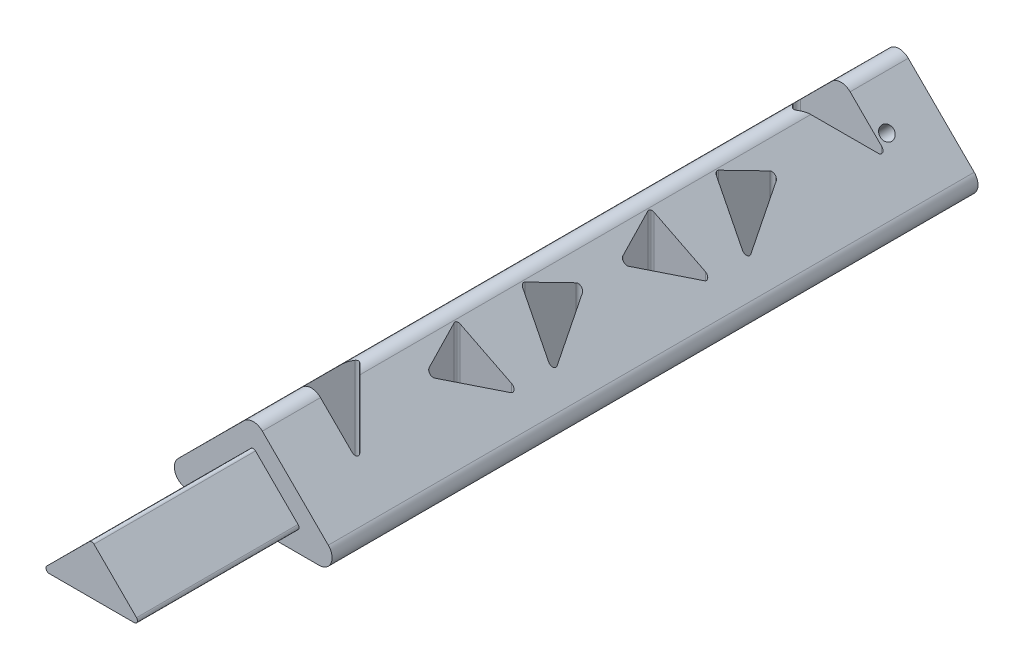
SolidWorks part; units mm, degrees
ref_plane "前视基准面" through (0, 0, 0) normal (0, 0, 1) x (1, 0, 0)
ref_plane "上视基准面" through (0, 0, 0) normal (0, 1, 0) x (1, 0, 0)
ref_plane "右视基准面" through (0, 0, 0) normal (1, 0, 0) x (0, 0, -1)
other "Configuration Table"
sketch "草图1" plane through (0, 0, 0) normal (0, 0, 1) x (1, 0, 0)
  line L0 (-30.1, 0) -> (30.1, 0)
  line L1 (30.1, 0) -> (0, 30.004)
  line L2 (0, 30.004) -> (-30.1, 0)
  dimension "D1" = 42.5
  dimension "D2" = 60.2
extrude "凸台-拉伸1" add sketch "草图1" along normal mid plane 200
fillet "圆角1" radius 4 3 edges at (0, 30.004, 0) (30.1, 0, 0) (-30.1, 0, 0)
sketch "草图2" plane through (0, 0, 100) normal (0, 0, 1) x (1, 0, 0)
  line L0 (15.5819, 6) -> (0, 21.5322)
  line L1 (0, 21.5322) -> (-15.5819, 6)
  line L2 (-15.5819, 6) -> (15.5819, 6)
  line L3 (23.2452, 6.8329) -> (2.8239, 27.1891)
  line L4 (-2.8239, 27.1891) -> (-23.2452, 6.8329)
  line L5 (-20.4213, 0) -> (20.4213, 0)
  line L6 (23.2452, 6.8329) -> (2.8239, 27.1891) construction
  line L7 (-2.8239, 27.1891) -> (-23.2452, 6.8329) construction
  line L8 (-20.4213, 0) -> (20.4213, 0) construction
  arc A0 (0, 21.5322) -> (0, 21.5322) centre (0, 21.5322) ccw
  arc A1 (-15.5819, 6) -> (-15.5819, 6) centre (-15.5819, 6) ccw
  arc A2 (15.5819, 6) -> (15.5819, 6) centre (15.5819, 6) ccw
  arc A3 (2.8239, 27.1891) -> (-2.8239, 27.1891) centre (0, 24.3562) ccw
  arc A4 (-23.2452, 6.8329) -> (-20.4213, 0) centre (-20.4213, 4) ccw
  arc A5 (20.4213, 0) -> (23.2452, 6.8329) centre (20.4213, 4) ccw
  arc A6 (2.8239, 27.1891) -> (-2.8239, 27.1891) centre (0, 24.3562) ccw construction
  arc A7 (-23.2452, 6.8329) -> (-20.4213, 0) centre (-20.4213, 4) ccw construction
  arc A8 (20.4213, 0) -> (23.2452, 6.8329) centre (20.4213, 4) ccw construction
  dimension "D1" = 0
  dimension "D2" = 6
extrude "凸台-拉伸2" add sketch "草图2" along normal blind 50
fillet "圆角2" radius 1 3 edges at (15.5819, 6, 125) (-15.5819, 6, 125) (0, 21.5322, 125)
sketch "草图3" plane through (0, 0, 0) normal (0, 1, 0) x (1, 0, 0)
  line L0 (-15, 82) -> (0, 67)
  line L1 (-2.8239, -100) -> (-2.8239, 100) construction
  line L2 (-15, 82) -> (15, 82)
  line L3 (15, 82) -> (0, 67)
  line L4 (-8, 55) -> (-18, 35)
  line L5 (-18, 35) -> (-2.8239, 40)
  line L6 (-2.8239, 40) -> (-8, 55)
  line L7 (0, -59.243) -> (0, 59.243) construction
  line L8 (2.8239, 40) -> (8, 55)
  line L9 (18, 35) -> (2.8239, 40)
  line L10 (8, 55) -> (18, 35)
  line L14 (-17.9681, 30) -> (0, 30) construction
  line L15 (2.8239, 100) -> (2.8239, -100) construction
  line L16 (8, 5) -> (18, 25)
  line L17 (18, 25) -> (2.8239, 20)
  line L18 (2.8239, 20) -> (8, 5)
  line L19 (-2.8239, 20) -> (-8, 5)
  line L20 (-18, 25) -> (-2.8239, 20)
  line L21 (-8, 5) -> (-18, 25)
  line L22 (23.2452, 100) -> (2.8239, 100) construction
  line L23 (0, 0) -> (91.7883, 0) construction
  line L24 (-17.9681, -30) -> (0, -30) construction
  line L25 (-8, -5) -> (-18, -25)
  line L26 (-18, -25) -> (-2.8239, -20)
  line L27 (-2.8239, -20) -> (-8, -5)
  line L28 (2.8239, -20) -> (8, -5)
  line L29 (18, -25) -> (2.8239, -20)
  line L30 (8, -5) -> (18, -25)
  line L31 (8, -55) -> (18, -35)
  line L32 (18, -35) -> (2.8239, -40)
  line L33 (2.8239, -40) -> (8, -55)
  line L34 (-2.8239, -40) -> (-8, -55)
  line L35 (-18, -35) -> (-2.8239, -40)
  line L36 (-8, -55) -> (-18, -35)
  line L37 (15, -82) -> (0, -67)
  line L38 (-15, -82) -> (15, -82)
  line L39 (-15, -82) -> (0, -67)
  point P32 (0, 82)
  dimension "D1" = 30
  dimension "D2" = 30
  dimension "D3" = 10
  dimension "D4" = 15
  dimension "D5" = 18
  dimension "D6" = 8
  dimension "D7" = 18
  dimension "D8" = 10
  dimension "D9" = 25
extrude "切除-拉伸1" cut sketch "草图3" along normal through all
fillet "圆角3" radius 1 30 edges at (0, 14.1781, -67) (-15, 7.5259, -82) (2.8239, 13.5946, -40) (8, 11.0148, -55) (18, 6.0307, -35) (-2.8239, 13.5946, -20) (-8, 11.0148, -5) (-18, 6.0307, -25) (2.8239, 13.5946, 20) (8, 11.0148, 5) (18, 6.0307, 25) (-2.8239, 13.5946, 40) (-8, 11.0148, 55) (-18, 6.0307, 35) (-15, 7.5259, 82) (0, 14.1781, 67) (15, 7.5259, 82) (2.8239, 13.5946, 40) (18, 6.0307, 35) (8, 11.0148, 55) (-2.8239, 13.5946, 20) (-18, 6.0307, 25) (-8, 11.0148, 5) (2.8239, 13.5946, -20) (18, 6.0307, -25) (8, 11.0148, -5) (-2.8239, 13.5946, -40) (-18, 6.0307, -35) (-8, 11.0148, -55) (15, 7.5259, -82)
sketch "草图4" plane through (-15.0019, 15.0499, 0) normal (-0.706, 0.7082, 0) x (0.7082, 0.706, 0)
  circle A0 centre (5.3551, 85) radius 2.1
  dimension "D1" = 4.2
extrude "切除-拉伸2" cut sketch "草图4" against normal up to next
mirror "镜向1" about plane through (0, 0, 0) normal (1, 0, 0) of "切除-拉伸2"
